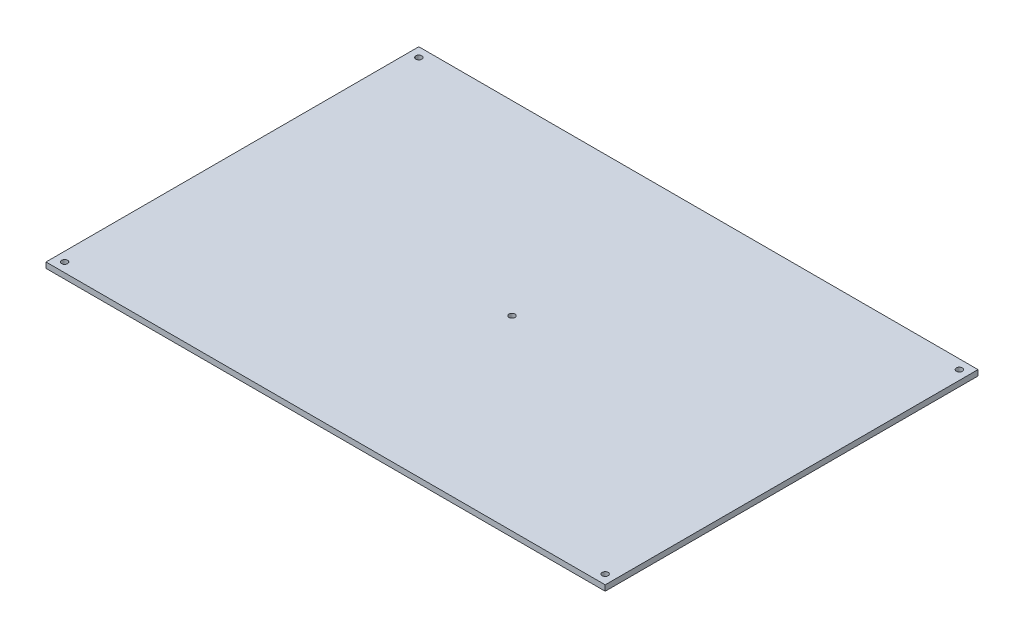
SolidWorks part; units mm, degrees
material "1060 Alloy"
ref_plane "Front Plane" through (0, 0, 0) normal (0, 0, 1) x (1, 0, 0)
ref_plane "Top Plane" through (0, 0, 0) normal (0, 1, 0) x (1, 0, 0)
ref_plane "Right Plane" through (0, 0, 0) normal (1, 0, 0) x (0, 0, -1)
ref_plane "Plane1"
sketch "Sketch1" plane through (0, 0, 0) normal (0, 1, 0) x (-1, 0, 0)
  line L0 (150, 100) -> (-150, -100) construction
  line L1 (150, -100) -> (-150, 100) construction
  line L2 (-150, -100) -> (150, -100)
  line L3 (150, -100) -> (150, 100)
  line L4 (150, 100) -> (-150, 100)
  line L5 (-150, 100) -> (-150, -100)
  point P0 (0, 0)
  dimension "D1" = 300
  dimension "D2" = 200
extrude "Extrusion1" add sketch "Sketch1" against normal blind 3
sketch "Sketch4" plane through (0, 0, 0) normal (0, 1, 0) x (1, 0, 0)
  line L0 (150, -100) -> (150, 100) construction
  line L1 (150, 100) -> (-150, 100) construction
  line L2 (0, 0) -> (0, 30) construction
  line L3 (0, 0) -> (30, 0) construction
  point P0 (145, 95)
  point P8 (145, -95)
  point P9 (-145, 95)
  point P11 (-145, -95)
  point P12 (0, -104.5)
  dimension "D1" = 5
  dimension "D2" = 5
hole_wizard "Ø3.2 (3.2) Diameter Hole1" positions "Sketch5" profile "Sketch6" hole size "Ø3.2" standard "ANSI Metric" end condition through all
sketch "Sketch5" plane through (0, 0, 0) normal (0, 1, 0) x (1, 0, 0)
  point P0 (-145, 95)
  point P3 (145, 95)
  point P6 (145, -95)
  point P9 (0, -104.5)
  point P12 (-145, -95)
  point P15 (0, 0)
sketch "Sketch6" plane through (-145, 0, -95) normal (1, 0, 0) x (0, 0, 1)
  line L0 (0, 0) -> (0, 3)
  line L1 (0, 3) -> (1.6, 3)
  line L2 (1.6, 3) -> (1.6, 0)
  line L5 (1.6, 0) -> (0, 0)
  line L11 (0, -6.35) -> (0, 107.95) construction
  dimension "Thru Hole Dia." = 3.2
  dimension "Thru Hole Depth" = 3
